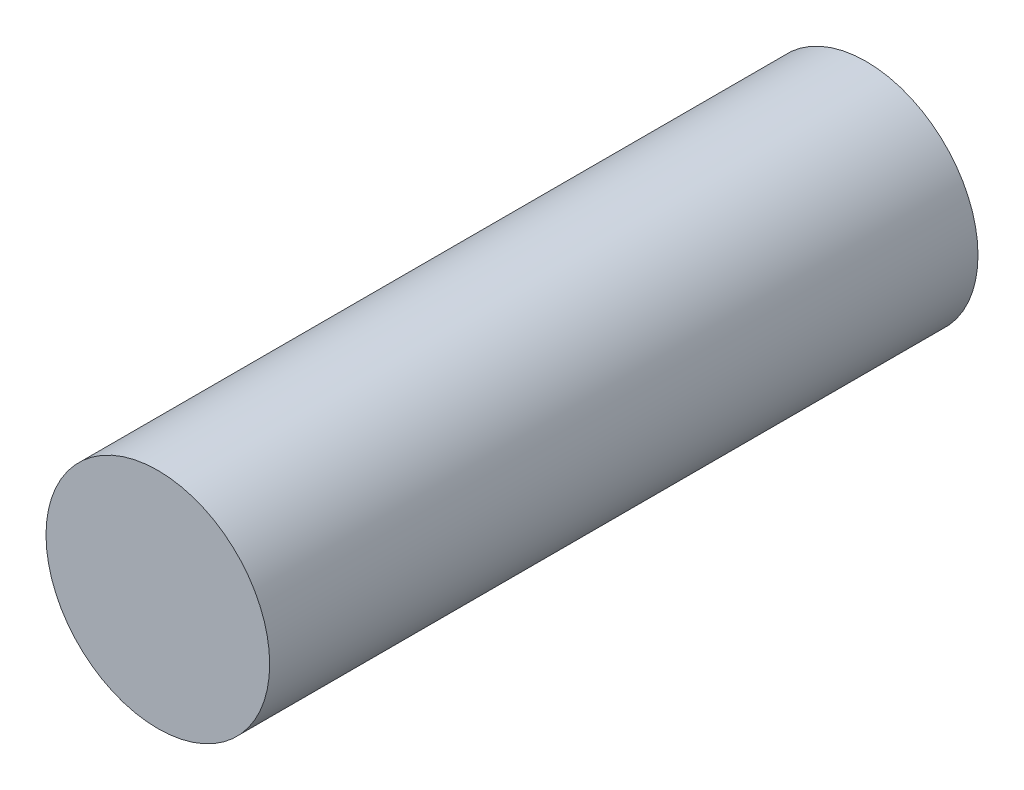
SolidWorks part; units mm, degrees
ref_plane "Front Plane" through (0, 0, 0) normal (0, 0, 1) x (1, 0, 0)
ref_plane "Top Plane" through (0, 0, 0) normal (0, 1, 0) x (1, 0, 0)
ref_plane "Right Plane" through (0, 0, 0) normal (1, 0, 0) x (0, 0, -1)
sketch "Sketch1" plane through (0, 0, 0) normal (0, 0, 1) x (1, 0, 0)
  circle A0 centre (-54.5716, 30.034) radius 30
sketch "Sketch2" plane through (0, 0, 0) normal (0, 0, 1) x (1, 0, 0)
  circle A0 centre (-54.5716, 30.034) radius 30
extrude "Boss-Extrude1" add sketch "Sketch2" along normal blind 190
